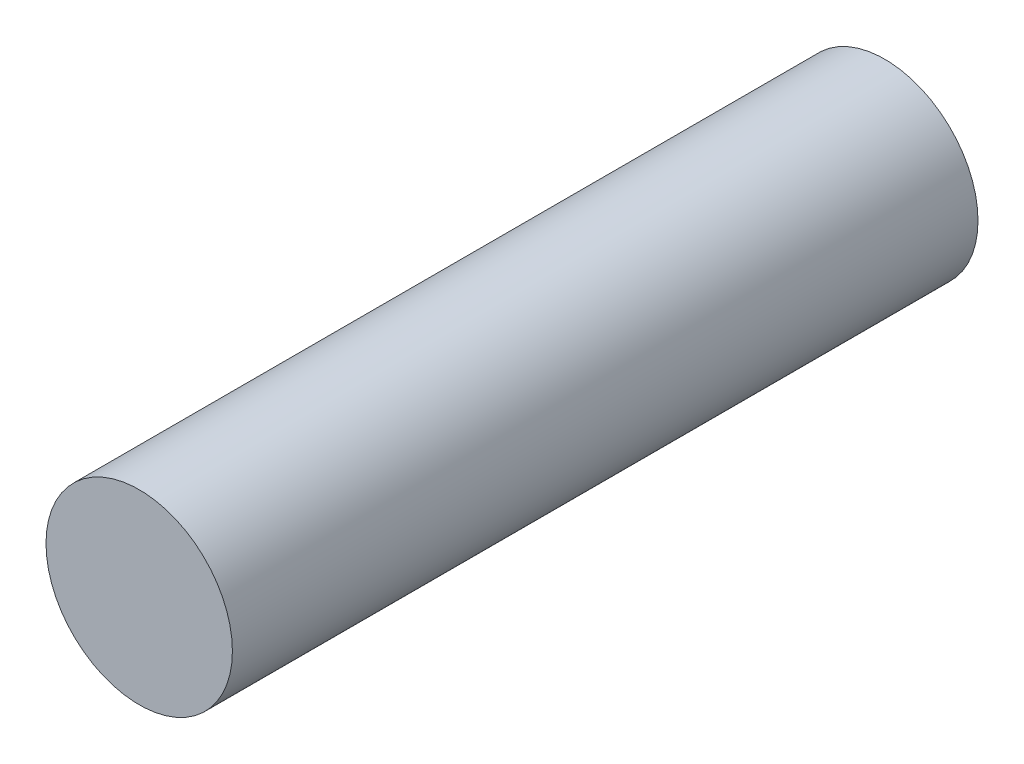
SolidWorks part; units mm, degrees
ref_plane "Front Plane" through (0, 0, 0) normal (0, 0, 1) x (1, 0, 0)
ref_plane "Top Plane" through (0, 0, 0) normal (0, 1, 0) x (1, 0, 0)
ref_plane "Right Plane" through (0, 0, 0) normal (1, 0, 0) x (0, 0, -1)
sketch "Dowel_diameter_6p35mm" plane through (0, 0, 0) normal (0, 0, 1) x (1, 0, 0)
  circle A0 centre (0, 0) radius 3.175
extrude "Dowel_length_25p4mm" add sketch "Dowel_diameter_6p35mm" along normal blind 25.4
